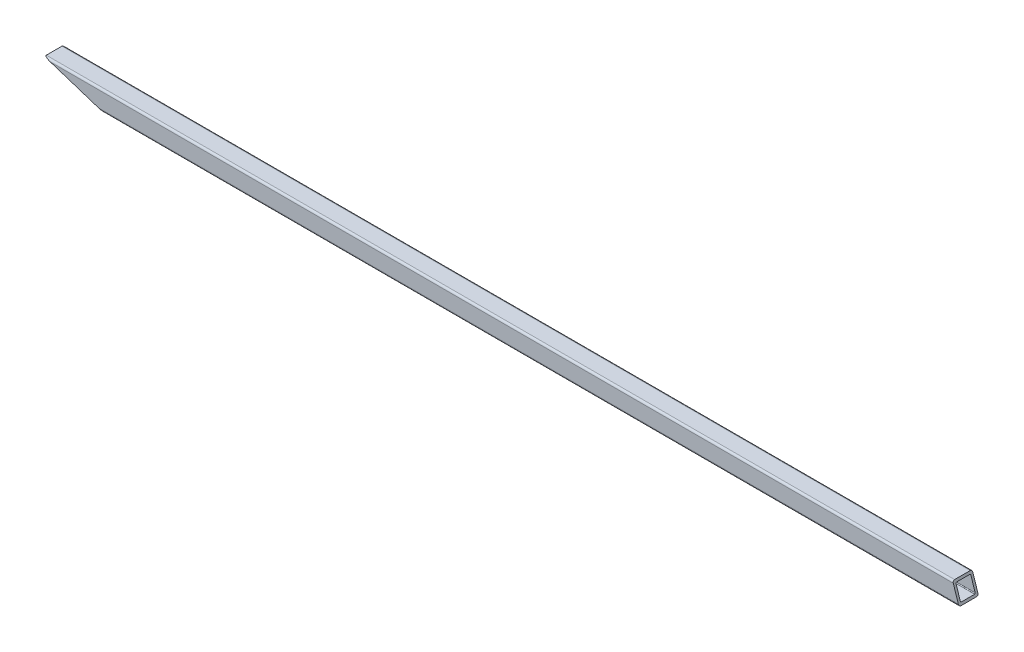
SolidWorks part; units mm, degrees
ref_plane "Front Plane" through (0, 0, 0) normal (0, 0, 1) x (1, 0, 0)
ref_plane "Top Plane" through (0, 0, 0) normal (0, 1, 0) x (1, 0, 0)
ref_plane "Right Plane" through (0, 0, 0) normal (1, 0, 0) x (0, 0, -1)
sketch "Sketch3" plane through (0, 0, 0) normal (1, 0, 0) x (0, 0, -1)
  line L1 (-12.7, 12.7) -> (12.7, 12.7)
  line L2 (-12.7, 12.7) -> (-12.7, -12.7)
  line L3 (-12.7, -12.7) -> (12.7, -12.7)
  line L4 (12.7, 12.7) -> (12.7, -12.7)
  line L5 (-12.7, 12.7) -> (12.7, -12.7) construction
  line L6 (-12.7, -12.7) -> (12.7, 12.7) construction
  line L7 (-9.652, -9.652) -> (9.652, -9.652)
  line L8 (-9.652, -9.652) -> (-9.652, 9.652)
  line L9 (-9.652, 9.652) -> (9.652, 9.652)
  line L10 (9.652, -9.652) -> (9.652, 9.652)
  line L11 (-9.652, -9.652) -> (9.652, 9.652) construction
  line L12 (-9.652, 9.652) -> (9.652, -9.652) construction
  point P0 (0, 0)
  point P6 (0, 0)
  dimension "D1" = 25.4
  dimension "D2" = 19.304
  dimension "D3" = 19.304
  dimension "D4" = 25.4
extrude "Boss-Extrude1" add sketch "Sketch3" against normal blind 1190.03
fillet "Fillet1" radius 2.5 4 edges at (-595.015, -12.7, -12.7) (-595.015, -12.7, 12.7) (-595.015, 12.7, -12.7) (-595.015, 12.7, 12.7)
fillet "Fillet2" radius 1 4 edges at (-595.015, -9.652, -9.652) (-595.015, 9.652, -9.652) (-595.015, 9.652, 9.652) (-595.015, -9.652, 9.652)
sketch "Sketch5" plane through (0, 0, -12.7) normal (0, 0, -1) x (-1, 0, 0)
  line L0 (1190.03, 12.7) -> (1111.8568, -12.7)
  line L1 (0, -12.7) -> (1190.03, -12.7) construction
  line L2 (1111.8568, -12.7) -> (1190.03, -12.7)
  line L3 (1190.03, -12.7) -> (1190.03, 12.7)
  line L4 (0, 12.7) -> (8.253, 12.7)
  line L5 (1190.03, 12.7) -> (0, 12.7) construction
  line L6 (8.253, 12.7) -> (0, -12.7)
  line L7 (0, -12.7) -> (0, 12.7)
  dimension "D1" = 18
  dimension "D2" = 18
extrude "Cut-Extrude1" cut sketch "Sketch5" against normal through all
